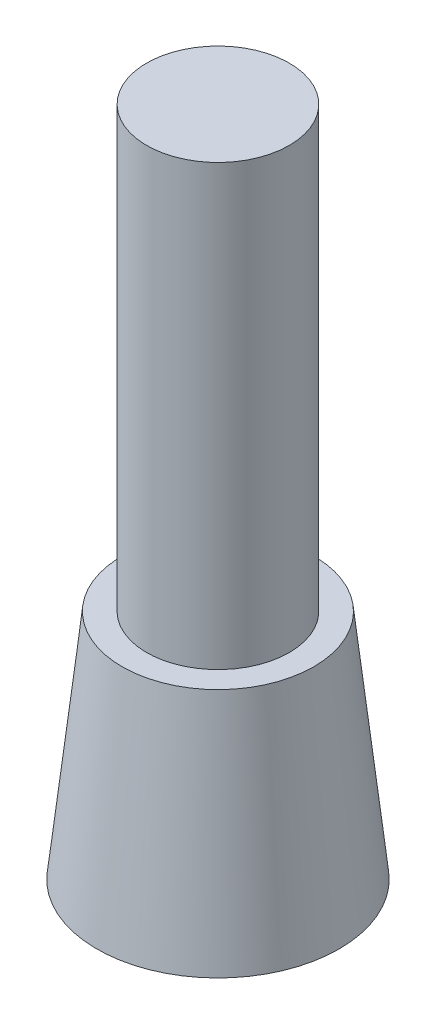
SolidWorks part; units mm, degrees
material "Alloy Steel"
ref_plane "Front Plane" through (0, 0, 0) normal (0, 0, 1) x (1, 0, 0)
ref_plane "Top Plane" through (0, 0, 0) normal (0, 1, 0) x (1, 0, 0)
ref_plane "Right Plane" through (0, 0, 0) normal (1, 0, 0) x (0, 0, -1)
sketch "Sketch1" plane through (0, 0, 0) normal (0, 0, 1) x (1, 0, 0)
  line L0 (0, 0) -> (0, 22.9362) construction
  line L1 (0, 22.9362) -> (0, 6.35)
  line L2 (0, 6.35) -> (1.5, 6.35)
  line L3 (1.5, 6.35) -> (1.5, 0)
  line L4 (1.5, 0) -> (4.1402, 0)
  line L5 (4.1402, 0) -> (3.2766, 7.9248)
  line L6 (3.2766, 7.9248) -> (2.4384, 7.9248)
  line L7 (2.4384, 7.9248) -> (2.4384, 22.9362)
  line L8 (2.4384, 22.9362) -> (0, 22.9362)
  dimension "D1" = 4.8768
  dimension "D2" = 3
  dimension "D3" = 22.9362
  dimension "D4" = 7.9248
  dimension "D5" = 6.5532
  dimension "D6" = 8.2804
  dimension "D7" = 6.35
  dimension "D8" = 83.781
revolve "Revolve1" add sketch "Sketch1" angle 360 about L0
